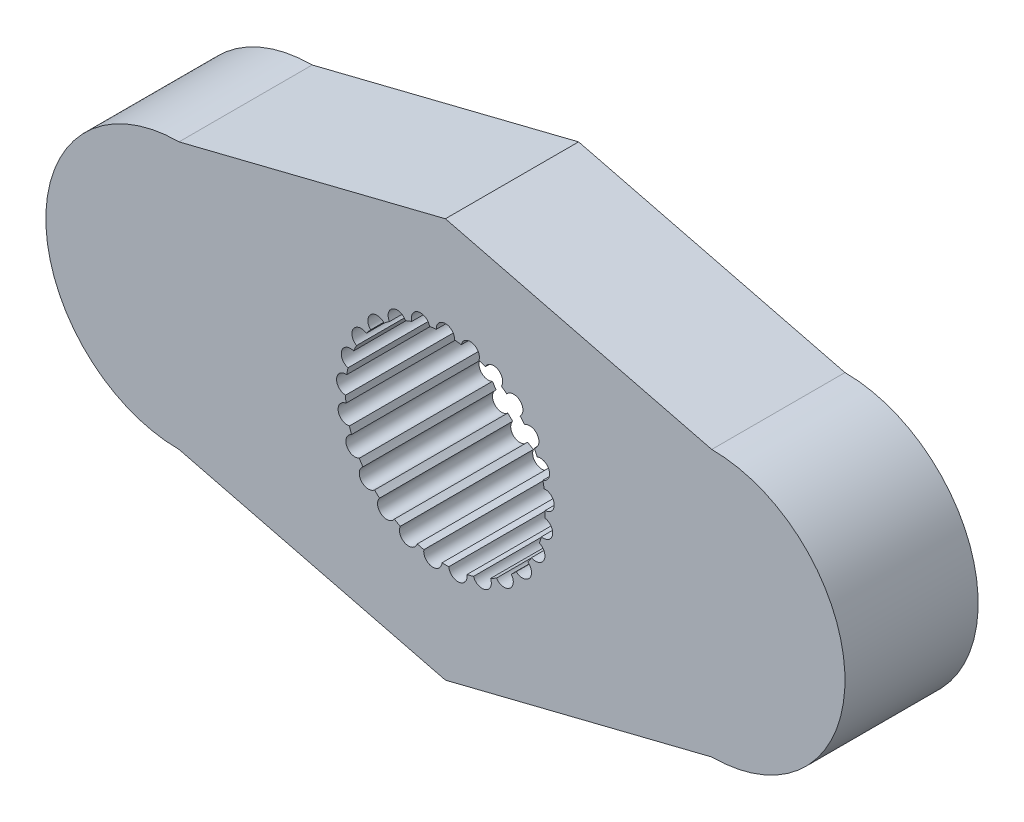
SolidWorks part; units mm, degrees
ref_plane "Ebene vorne" through (0, 0, 0) normal (0, 0, 1) x (1, 0, 0)
ref_plane "Ebene oben" through (0, 0, 0) normal (0, 1, 0) x (1, 0, 0)
ref_plane "Ebene rechts" through (0, 0, 0) normal (1, 0, 0) x (0, 0, -1)
sketch "Skizze1" plane through (0, 0, 0) normal (0, 0, 1) x (1, 0, 0)
  line L1 (-8, 4) -> (0, 6)
  line L6 (-8, -4) -> (0, -6)
  line L7 (8, -4) -> (0, -6)
  line L8 (8, 4) -> (0, 6)
  arc A7 (-8, 4) -> (-8, -4) centre (-8, 0) ccw
  arc A10 (8, 4) -> (8, -4) centre (8, 0) cw
  arc A65 (1.1985, 2.7502) -> (1.009, 2.8252) centre (0, 0) ccw
  arc A66 (0.2747, 2.9874) -> (-0.2747, 2.9874) centre (0, 3) ccw
  arc A67 (1.009, 2.8252) -> (0.4769, 2.9619) centre (0.7461, 2.9057) ccw
  arc A68 (1.6799, 2.4855) -> (1.1985, 2.7502) centre (1.4453, 2.6289) ccw
  arc A69 (2.2453, 1.9897) -> (1.8448, 2.3658) centre (2.0536, 2.1869) ccw
  arc A70 (2.6695, 1.3688) -> (2.3751, 1.8327) centre (2.533, 1.6075) ccw
  arc A71 (2.9261, 0.6619) -> (2.7563, 1.1844) centre (2.8532, 0.9271) ccw
  arc A72 (2.9988, -0.0866) -> (2.9643, 0.4617) centre (2.9941, 0.1884) ccw
  arc A73 (2.883, -0.8296) -> (2.986, -0.2899) centre (2.9469, -0.5621) ccw
  arc A74 (2.5861, -1.5205) -> (2.82, -1.0234) centre (2.7145, -1.2773) ccw
  arc A75 (2.1267, -2.1159) -> (2.4769, -1.6926) centre (2.3115, -1.9123) ccw
  arc A76 (1.5337, -2.5783) -> (1.9782, -2.2554) centre (1.7634, -2.4271) ccw
  arc A77 (0.8443, -2.8787) -> (1.3552, -2.6765) centre (1.1044, -2.7893) ccw
  arc A78 (0.1019, -2.9983) -> (0.647, -2.9294) centre (0.376, -2.9763) ccw
  arc A79 (-0.647, -2.9294) -> (-0.1019, -2.9983) centre (-0.376, -2.9763) ccw
  arc A80 (-1.3552, -2.6765) -> (-0.8443, -2.8787) centre (-1.1044, -2.7893) ccw
  arc A81 (-1.9782, -2.2554) -> (-1.5337, -2.5783) centre (-1.7634, -2.4271) ccw
  arc A82 (-2.4769, -1.6926) -> (-2.1267, -2.1159) centre (-2.3115, -1.9123) ccw
  arc A83 (-2.82, -1.0234) -> (-2.5861, -1.5205) centre (-2.7145, -1.2773) ccw
  arc A84 (-2.986, -0.2899) -> (-2.883, -0.8296) centre (-2.9469, -0.5621) ccw
  arc A85 (-2.9643, 0.4617) -> (-2.9988, -0.0866) centre (-2.9941, 0.1884) ccw
  arc A86 (-2.7563, 1.1844) -> (-2.9261, 0.6619) centre (-2.8532, 0.9271) ccw
  arc A87 (-2.3751, 1.8327) -> (-2.6695, 1.3688) centre (-2.533, 1.6075) ccw
  arc A88 (-1.8448, 2.3658) -> (-2.2453, 1.9897) centre (-2.0536, 2.1869) ccw
  arc A89 (-1.1985, 2.7502) -> (-1.6799, 2.4855) centre (-1.4453, 2.6289) ccw
  arc A90 (-0.4769, 2.9619) -> (-1.009, 2.8252) centre (-0.7461, 2.9057) ccw
  arc A91 (0.4769, 2.9619) -> (0.2747, 2.9874) centre (0, 0) ccw
  arc A92 (-0.2747, 2.9874) -> (-0.4769, 2.9619) centre (0, 0) ccw
  arc A93 (-1.009, 2.8252) -> (-1.1985, 2.7502) centre (0, 0) ccw
  arc A94 (-1.6799, 2.4855) -> (-1.8448, 2.3658) centre (0, 0) ccw
  arc A95 (-2.2453, 1.9897) -> (-2.3751, 1.8327) centre (0, 0) ccw
  arc A96 (-2.6695, 1.3688) -> (-2.7563, 1.1844) centre (0, 0) ccw
  arc A97 (-2.9261, 0.6619) -> (-2.9643, 0.4617) centre (0, 0) ccw
  arc A98 (-2.9988, -0.0866) -> (-2.986, -0.2899) centre (0, 0) ccw
  arc A99 (-2.883, -0.8296) -> (-2.82, -1.0234) centre (0, 0) ccw
  arc A100 (-2.5861, -1.5205) -> (-2.4769, -1.6926) centre (0, 0) ccw
  arc A101 (-2.1267, -2.1159) -> (-1.9782, -2.2554) centre (0, 0) ccw
  arc A102 (-1.5337, -2.5783) -> (-1.3552, -2.6765) centre (0, 0) ccw
  arc A103 (-0.8443, -2.8787) -> (-0.647, -2.9294) centre (0, 0) ccw
  arc A104 (-0.1019, -2.9983) -> (0.1019, -2.9983) centre (0, 0) ccw
  arc A105 (0.647, -2.9294) -> (0.8443, -2.8787) centre (0, 0) ccw
  arc A106 (1.3552, -2.6765) -> (1.5337, -2.5783) centre (0, 0) ccw
  arc A107 (1.9782, -2.2554) -> (2.1267, -2.1159) centre (0, 0) ccw
  arc A108 (2.4769, -1.6926) -> (2.5861, -1.5205) centre (0, 0) ccw
  arc A109 (2.82, -1.0234) -> (2.883, -0.8296) centre (0, 0) ccw
  arc A110 (2.986, -0.2899) -> (2.9988, -0.0866) centre (0, 0) ccw
  arc A111 (2.9643, 0.4617) -> (2.9261, 0.6619) centre (0, 0) ccw
  arc A112 (2.7563, 1.1844) -> (2.6695, 1.3688) centre (0, 0) ccw
  arc A113 (2.3751, 1.8327) -> (2.2453, 1.9897) centre (0, 0) ccw
  arc A114 (1.8448, 2.3658) -> (1.6799, 2.4855) centre (0, 0) ccw
  point P65 (0, 0)
  point P69 (0, 0)
  dimension "D2" = 8
  dimension "D3" = 6
  dimension "D4" = 0.55
  dimension "D5" = 25
extrude "Grundkörper" add sketch "Skizze1" along normal blind 4
